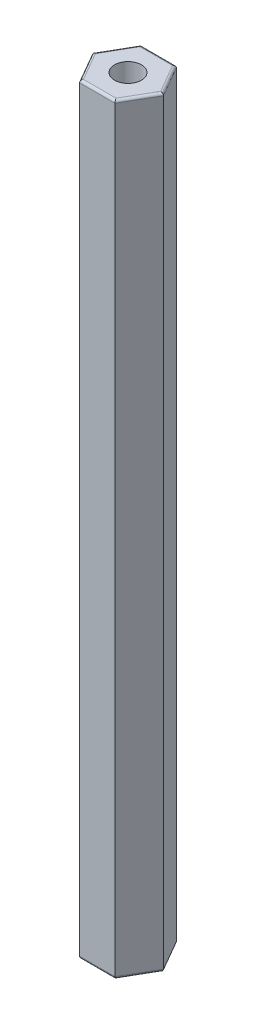
SolidWorks part; units mm, degrees
material "201.0-T43 Molde de fundição com isolamento (SS)"
ref_plane "Plano frontal" through (0, 0, 0) normal (0, 0, 1) x (1, 0, 0)
ref_plane "Plano superior" through (0, 0, 0) normal (0, 1, 0) x (1, 0, 0)
ref_plane "Plano direito" through (0, 0, 0) normal (1, 0, 0) x (0, 0, -1)
sketch "Esboço1" plane through (0, 0, 0) normal (0, 1, 0) x (1, 0, 0)
  line L1 (2.8868, 0) -> (1.4434, 2.5)
  line L2 (1.4434, 2.5) -> (-1.4434, 2.5)
  line L3 (-1.4434, 2.5) -> (-2.8868, 0)
  line L4 (-2.8868, 0) -> (-1.4434, -2.5)
  line L5 (-1.4434, -2.5) -> (1.4434, -2.5)
  line L6 (1.4434, -2.5) -> (2.8868, 0)
  circle A0 centre (0, 0) radius 2.5 construction
  dimension "D1" = 5
extrude "Ressalto-extrusão1" add sketch "Esboço1" along normal blind 62
fillet "Filete1" radius 0.2 12 edges at (0, 62, -2.5) (-2.1651, 62, -1.25) (-2.1651, 62, 1.25) (0, 62, 2.5) (2.1651, 62, 1.25) (2.1651, 62, -1.25) (0, 0, 2.5) (-2.1651, 0, 1.25) (-2.1651, 0, -1.25) (0, 0, -2.5) (2.1651, 0, -1.25) (2.1651, 0, 1.25)
sketch "Esboço2" plane through (0, 0, 0) normal (0, -1, 0) x (1, 0, 0)
  circle A0 centre (0, 0) radius 1.0922
  dimension "D1" = 2.1844
sketch "Esboço3" plane through (0, 62, 0) normal (0, 1, 0) x (1, 0, 0)
  circle A0 centre (0, 0) radius 1.0922
extrude "Corte-extrusão1" cut sketch "Esboço3" against normal blind 5
extrude "Corte-extrusão2" cut sketch "Esboço2" against normal blind 5 contours A0
